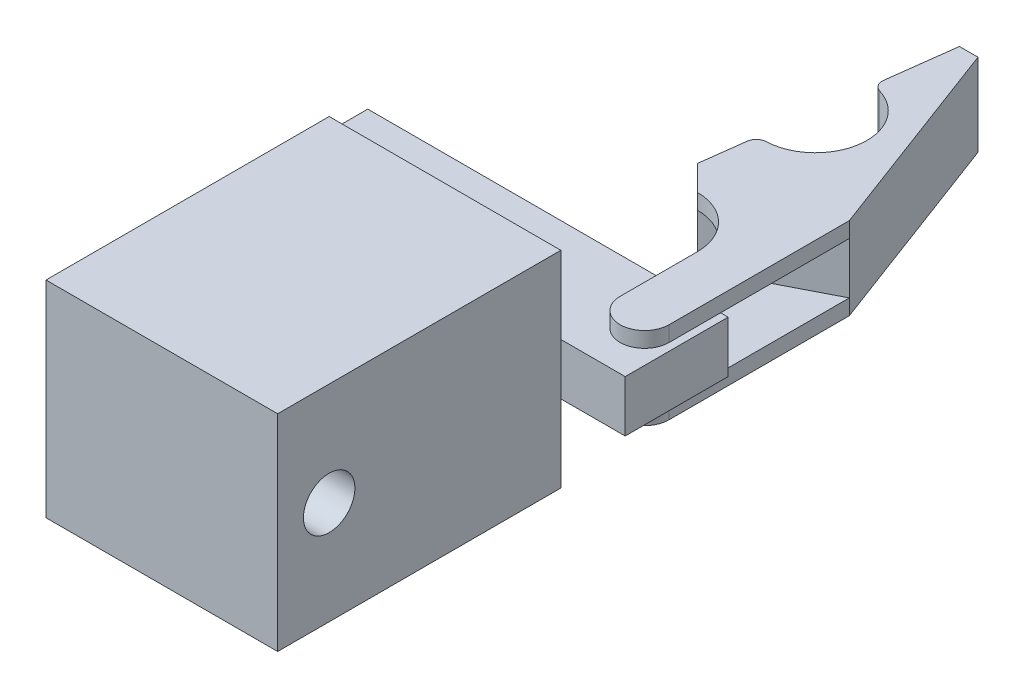
SolidWorks part; units mm, degrees
ref_plane "Front Plane" through (0, 0, 0) normal (0, 0, 1) x (1, 0, 0)
ref_plane "Top Plane" through (0, 0, 0) normal (0, 1, 0) x (1, 0, 0)
ref_plane "Right Plane" through (0, 0, 0) normal (1, 0, 0) x (0, 0, -1)
sketch "Sketch1" plane through (0, 0, 0) normal (0, 1, 0) x (1, 0, 0)
  line L1 (-22.5, -27.5) -> (22.5, -27.5)
  line L2 (-22.5, -27.5) -> (-22.5, 27.5)
  line L3 (-22.5, 27.5) -> (22.5, 27.5)
  line L4 (22.5, -27.5) -> (22.5, 27.5)
  line L5 (-22.5, -27.5) -> (22.5, 27.5) construction
  line L6 (-22.5, 27.5) -> (22.5, -27.5) construction
  point P0 (0, 0)
  dimension "D1" = 45
  dimension "D2" = 55
extrude "Boss-Extrude1" add sketch "Sketch1" along normal blind 40
sketch "Sketch2" plane through (22.5, 0, 0) normal (1, 0, 0) x (0, 0, -1)
  line L0 (-27.5, 40) -> (-27.5, 0) construction
  circle A0 centre (-17.5, 20) radius 5
  point P5 (-27.5, 20)
  dimension "D1" = 10
  dimension "D2" = 10
extrude "Cut-Extrude1" cut sketch "Sketch2" against normal up to surface (45 mm away) contours A0 up to face at (-22.5, 20, 0)
sketch "Sketch3" plane through (0, 0, -27.5) normal (0, 0, -1) x (-1, 0, 0)
  line L5 (-22.5, 0) -> (22.5, 0) construction
  line L6 (-35, 15) -> (35, 15)
  line L7 (-35, 15) -> (-35, 25)
  line L8 (-35, 25) -> (35, 25)
  line L9 (35, 15) -> (35, 25)
  line L10 (-35, 15) -> (35, 25) construction
  line L11 (-35, 25) -> (35, 15) construction
  point P0 (-3.8132, 20)
  point P1 (0, 20)
  point P9 (0, 0)
  dimension "D2" = 10
  dimension "D1" = 70
extrude "Boss-Extrude2" add sketch "Sketch3" along normal blind 20
sketch "Sketch6" plane through (0, 25, 0) normal (0, 1, 0) x (1, 0, 0)
  line L0 (35, 47.5) -> (35, 27.5) construction
  line L1 (-35, 47.5) -> (-35, 27.5) construction
  circle A0 centre (28.7714, 37.5) radius 1.5
  circle A1 centre (-27.7827, 37.5) radius 1.5
  point P4 (0, 0)
  point P7 (35, 37.5)
  point P8 (0, 0)
  point P11 (-35, 37.5)
  dimension "D1" = 3
  dimension "D2" = 3
extrude "Cut-Extrude3" cut sketch "Sketch6" against normal up to surface (10 mm away) up to face at (0, 15, -34.1667)
sketch "Sketch7" plane through (0, 25, 0) normal (0, 1, 0) x (1, 0, 0)
  line L0 (18.5339, 112.5) -> (14.9339, 112.5)
  line L1 (14.9339, 112.5) -> (13.262, 99.4387)
  line L2 (10.2575, 75.9659) -> (9.1551, 67.3537)
  line L3 (9.1551, 67.3537) -> (14.0089, 62.5)
  line L4 (24.0089, 52.5) -> (24.0089, 37.5)
  line L5 (33.5339, 37.5) -> (33.5339, 72.5)
  line L6 (33.5339, 72.5) -> (18.5339, 112.5)
  arc A0 (13.262, 99.4387) -> (14.6648, 97.271) centre (15.2458, 99.1848) ccw
  arc A1 (12.1611, 77.7104) -> (14.6648, 97.271) centre (11.7598, 87.7023) ccw
  arc A2 (12.1611, 77.7104) -> (10.2575, 75.9659) centre (12.2413, 75.712) ccw
  arc A3 (24.0089, 52.5) -> (14.0089, 62.5) centre (14.0089, 52.5) ccw
  arc A4 (24.0089, 37.5) -> (28.7714, 32.7375) centre (28.7714, 37.5) ccw
  arc A5 (28.7714, 32.7375) -> (33.5339, 37.5) centre (28.7714, 37.5) ccw
extrude "Boss-Extrude4" add sketch "Sketch7" along normal blind 3
sketch "Sketch8" plane through (0, 25, 0) normal (0, -1, 0) x (1, 0, 0)
  line L0 (33.5339, -72.5) -> (14.0089, -62.5)
  line L8 (33.5339, -72.5) -> (33.5339, -47.5)
  line L9 (33.5339, -47.5) -> (24.0089, -47.5)
  line L10 (24.0089, -47.5) -> (24.0089, -52.5)
  line L11 (14.0089, -62.5) -> (9.1551, -67.3537)
  line L12 (9.1551, -67.3537) -> (10.2575, -75.9659)
  line L13 (13.262, -99.4387) -> (14.9339, -112.5)
  line L14 (14.9339, -112.5) -> (18.5339, -112.5)
  line L15 (18.5339, -112.5) -> (33.5339, -72.5)
  line L16 (33.5339, -72.5) -> (33.5339, -47.5)
  line L17 (33.5339, -47.5) -> (24.0089, -47.5)
  line L18 (24.0089, -47.5) -> (24.0089, -52.5)
  line L19 (14.0089, -62.5) -> (9.1551, -67.3537)
  line L20 (9.1551, -67.3537) -> (10.2575, -75.9659)
  line L21 (13.262, -99.4387) -> (14.9339, -112.5)
  line L22 (14.9339, -112.5) -> (18.5339, -112.5)
  line L23 (18.5339, -112.5) -> (33.5339, -72.5)
  arc A4 (14.0089, -62.5) -> (24.0089, -52.5) centre (14.0089, -52.5) ccw
  arc A5 (10.2575, -75.9659) -> (12.1611, -77.7104) centre (12.2413, -75.712) ccw
  arc A6 (14.6648, -97.271) -> (12.1611, -77.7104) centre (11.7598, -87.7023) ccw
  arc A7 (14.6648, -97.271) -> (13.262, -99.4387) centre (15.2458, -99.1848) ccw
  arc A8 (14.0089, -62.5) -> (24.0089, -52.5) centre (14.0089, -52.5) ccw
  arc A9 (10.2575, -75.9659) -> (12.1611, -77.7104) centre (12.2413, -75.712) ccw
  arc A10 (14.6648, -97.271) -> (12.1611, -77.7104) centre (11.7598, -87.7023) ccw
  arc A11 (14.6648, -97.271) -> (13.262, -99.4387) centre (15.2458, -99.1848) ccw
  line M17 (14.0089, -62.5) -> (9.1551, -67.3537)
  line M18 (9.1551, -67.3537) -> (10.2575, -75.9659)
  arc M19 (10.2575, -75.9659) -> (12.1611, -77.7104) centre (12.2413, -75.712) ccw
  arc M20 (12.1611, -77.7104) -> (14.6648, -97.271) centre (11.7598, -87.7023) cw
  arc M21 (14.6648, -97.271) -> (13.262, -99.4387) centre (15.2458, -99.1848) ccw
  line M22 (13.262, -99.4387) -> (14.9339, -112.5)
  line M23 (14.9339, -112.5) -> (18.5339, -112.5)
  line M24 (18.5339, -112.5) -> (33.5339, -72.5)
  dimension "D1" = 0
extrude "Boss-Extrude5" add sketch "Sketch8" along normal blind 10 contours L0 M24 M17 M18 M19 M20 M21 M22 M23
ref_plane "Plane1" through (0, 20, 0) normal (0, 1, 0) x (1, 0, 0)
mirror "Mirror1" about plane through (0, 20, 0) normal (0, 1, 0) of "Boss-Extrude4"
